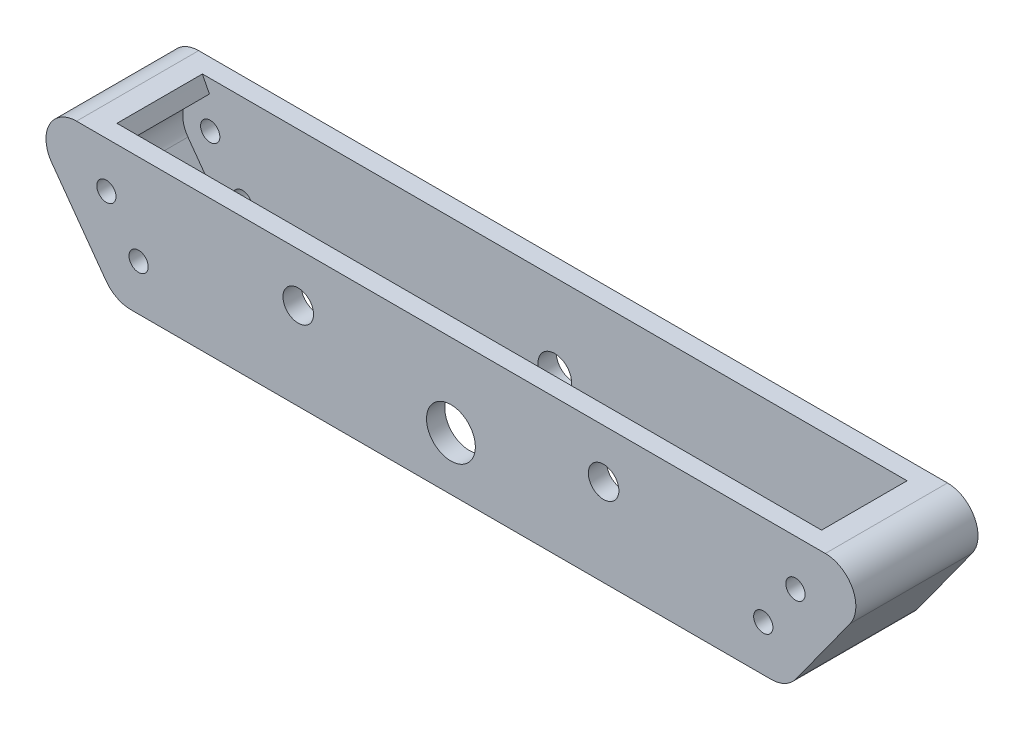
SolidWorks part; units mm, degrees
ref_plane "Front Plane" through (0, 0, 0) normal (0, 0, 1) x (1, 0, 0)
ref_plane "Top Plane" through (0, 0, 0) normal (0, 1, 0) x (1, 0, 0)
ref_plane "Right Plane" through (0, 0, 0) normal (1, 0, 0) x (0, 0, -1)
sketch "Sketch1" plane through (0, 0, 0) normal (0, 0, 1) x (1, 0, 0)
  line L0 (0, 0) -> (0, -62.5) construction
  line L1 (-71.0874, -27.7045) -> (0, -27.7045) construction
  line L2 (0, -50) -> (-54.9811, -50) construction
  line L3 (-54.9811, -50) -> (-71.0874, -27.7045) construction
  line L4 (-56.4171, -35.2045) -> (-51.1468, -42.5) construction
  line L5 (-71.0874, -27.7045) -> (-54.9811, -50)
  line L6 (-54.9811, -50) -> (-39.95, -50)
  line L7 (-71.0874, -27.7045) -> (-57.6928, -27.7045)
  line L8 (54.9811, -50) -> (39.95, -50)
  line L9 (71.0874, -27.7045) -> (54.9811, -50)
  line L10 (71.0874, -27.7045) -> (57.6928, -27.7045)
  line L11 (-58.7994, -31.3868) -> (-56.5441, -29.9795)
  line L12 (48.7646, -46.3177) -> (45.9424, -44.5566)
  line L13 (-56.4171, -35.2045) -> (0, 0) construction
  line L14 (-60.0649, -37.8397) -> (-54.7946, -45.1351)
  line L15 (-48.7646, -46.3177) -> (-45.9424, -44.5566)
  line L16 (60.0649, -37.8397) -> (54.7946, -45.1351)
  line L17 (58.7994, -31.3868) -> (56.5441, -29.9795)
  circle A0 centre (0, 0) radius 62.5 construction
  circle A2 centre (0, -41.25) radius 4
  circle A3 centre (-56.4171, -35.2045) radius 4 construction
  circle A4 centre (-51.1468, -42.5) radius 4 construction
  circle A5 centre (-56.4171, -35.2045) radius 1.575
  circle A6 centre (-51.1468, -42.5) radius 1.575
  circle A7 centre (0, -41.25) radius 15
  circle A8 centre (0, 0) radius 55.5 construction
  circle A9 centre (0, 0) radius 56.25 construction
  circle A10 centre (0, 0) radius 64 construction
  arc A11 (-57.6928, -27.7045) -> (-39.95, -50) centre (0, 0) ccw
  arc A12 (57.6928, -27.7045) -> (39.95, -50) centre (0, 0) cw
  circle A13 centre (51.1468, -42.5) radius 1.575
  circle A14 centre (56.4171, -35.2045) radius 1.575
  circle A15 centre (-56.4171, -35.2045) radius 4.5 construction
  arc A16 (-58.7994, -31.3868) -> (-60.0649, -37.8397) centre (-56.4171, -35.2045) ccw
  circle A17 centre (-51.1468, -42.5) radius 4.5 construction
  arc A18 (-48.7646, -46.3177) -> (-54.7946, -45.1351) centre (-51.1468, -42.5) cw
  arc A19 (48.7646, -46.3177) -> (54.7946, -45.1351) centre (51.1468, -42.5) ccw
  arc A20 (58.7994, -31.3868) -> (60.0649, -37.8397) centre (56.4171, -35.2045) cw
  dimension "D1" = 125
  dimension "D3" = 8
  dimension "D4" = 8
  dimension "D9" = 3.15
  dimension "D11" = 30
  dimension "D12" = 112.5
  dimension "D13" = 128
  dimension "D14" = 9
  dimension "D15" = 9
  dimension "D5" = 9
  dimension "D6" = 20
  dimension "D7" = 7.5
  dimension "D8" = 7.5
  dimension "D10" = 7.5
  dimension "D2" = 7
extrude "Boss-Extrude1" add sketch "Sketch1" along normal mid plane 14 contours A11 L7 L5 L6 A6 A5 | L10 A12 L8 L9 A13 A14
sketch "Sketch2" plane through (0, 0, 7) normal (0, 0, 1) x (1, 0, 0)
  line L0 (-54.9811, -50) -> (54.9811, -50)
  line L1 (54.9811, -50) -> (71.0874, -27.7045)
  line L2 (71.0874, -27.7045) -> (-71.0874, -27.7045)
  line L3 (-71.0874, -27.7045) -> (-54.9811, -50)
  circle A0 centre (0, -41.25) radius 4 construction
  circle A1 centre (0, -41.25) radius 4
  circle A10 centre (-51.1468, -42.5) radius 1.575 construction
  circle A11 centre (-56.4171, -35.2045) radius 1.575 construction
  circle A12 centre (-51.1468, -42.5) radius 1.575
  circle A13 centre (-56.4171, -35.2045) radius 1.575
  circle A14 centre (56.4171, -35.2045) radius 1.575 construction
  circle A15 centre (51.1468, -42.5) radius 1.575 construction
  circle A16 centre (56.4171, -35.2045) radius 1.575
  circle A17 centre (51.1468, -42.5) radius 1.575
extrude "Boss-Extrude2" add sketch "Sketch2" along normal blind 3
mirror "Mirror2" about plane through (0, 0, 0) normal (0, 0, 1) of "Boss-Extrude2"
fillet "Fillet1" radius 5 4 edges at (-54.9811, -50, 0) (54.9811, -50, 0) (71.0874, -27.7045, 0) (-71.0874, -27.7045, 0)
fillet "Fillet2" radius 1 2 edges at (39.95, -50, 0) (-39.95, -50, 0)
sketch "Sketch3" plane through (0, 0, -10) normal (0, 0, -1) x (-1, 0, 0)
  circle A0 centre (0, -41.25) radius 2.75
  circle A1 centre (0, -41.25) radius 6.0148
  dimension "D1" = 5.5
extrude "Boss-Extrude3" add sketch "Sketch3" against normal up to surface (3 mm away) up to face at (0, -40.2617, -7)
sketch "Sketch4" plane through (0, 0, 10) normal (0, 0, 1) x (1, 0, 0)
  line L0 (0, -27.7045) -> (0, -50) construction
  line L1 (-71.0874, -27.7045) -> (0, -27.7045) construction
  circle A0 centre (-25, -35.7045) radius 2.5
  circle A1 centre (25, -35.7045) radius 2.5
  dimension "D1" = 5
  dimension "D2" = 8
  dimension "D3" = 25
extrude "Cut-Extrude1" cut sketch "Sketch4" against normal blind 10
equation "\"D12@Sketch1\"=75*1.5"
equation "\"D11@Sketch1\"=20*1.5"
